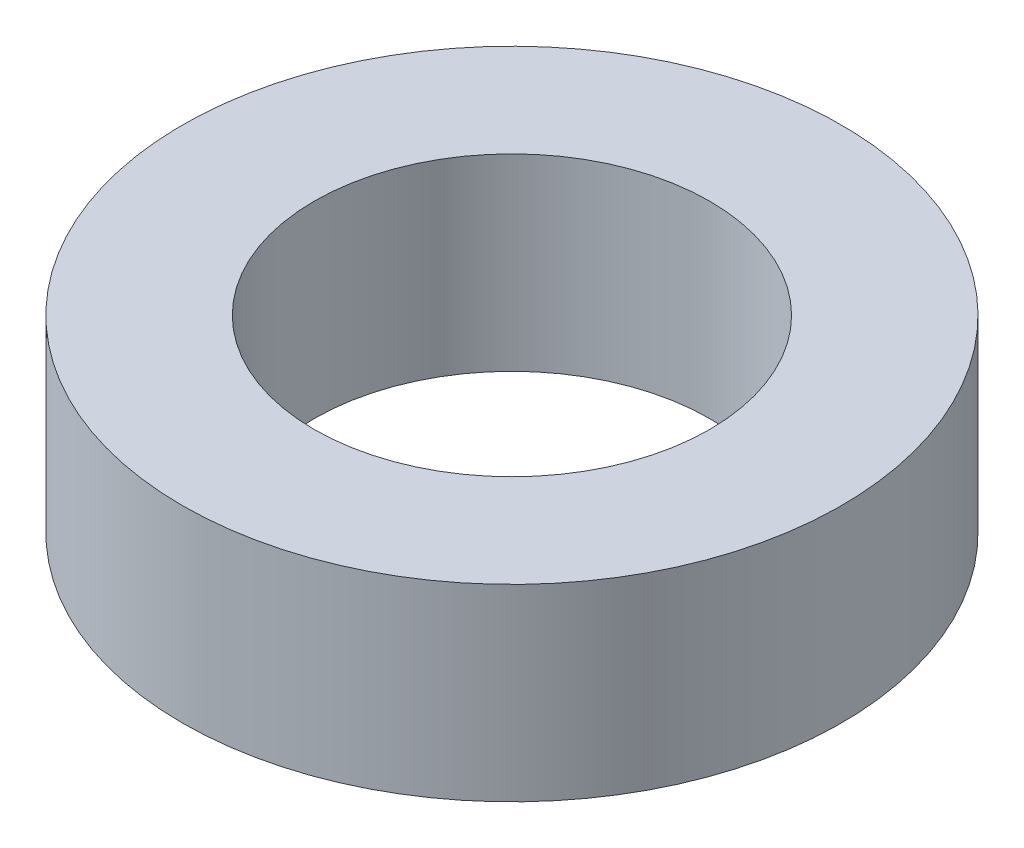
SolidWorks part; units mm, degrees
ref_plane "前视" through (0, 0, 0) normal (0, 0, 1) x (1, 0, 0)
ref_plane "上视" through (0, 0, 0) normal (0, 1, 0) x (1, 0, 0)
ref_plane "右视" through (0, 0, 0) normal (1, 0, 0) x (0, 0, -1)
sketch "草图1" plane through (0, 0, 0) normal (0, 1, 0) x (1, 0, 0)
  circle A0 centre (0, 0) radius 3.5
  circle A1 centre (0, 0) radius 2.1
  dimension "D1" = 4.2
  dimension "D2" = 7
extrude "凸台-拉伸1" add sketch "草图1" along normal blind 2
